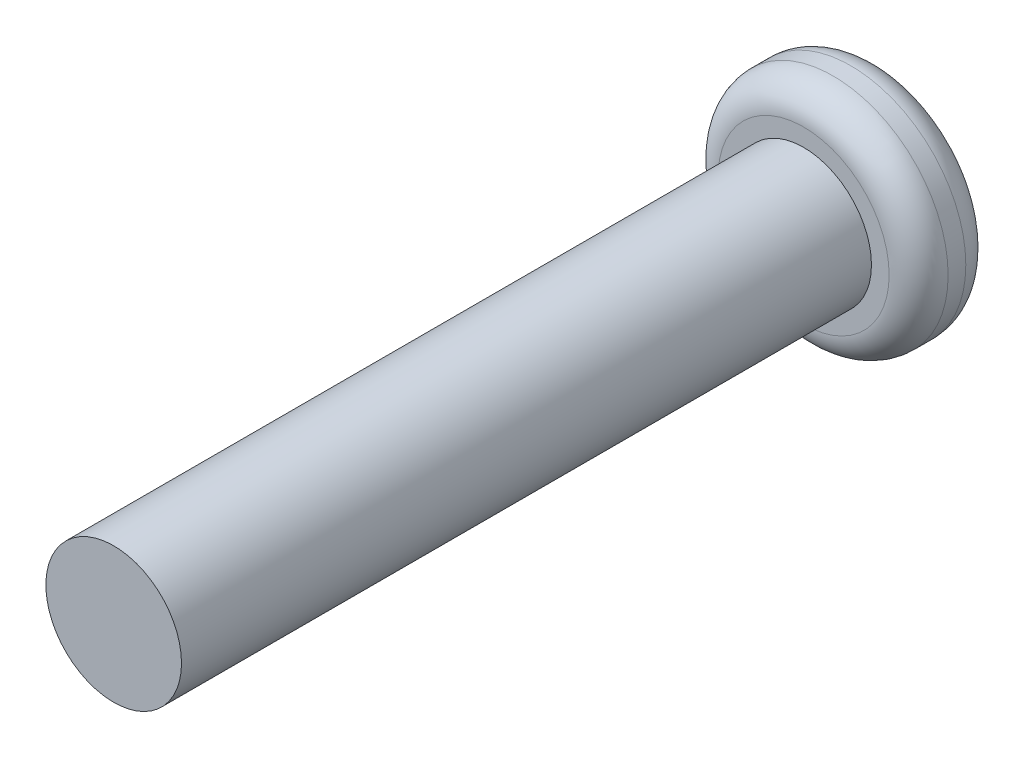
SolidWorks part; units mm, degrees
material "AISI 316 Annealed Stainless Steel Bar (SS)"
ref_plane "Front Plane" through (0, 0, 0) normal (0, 0, 1) x (1, 0, 0)
ref_plane "Top Plane" through (0, 0, 0) normal (0, 1, 0) x (1, 0, 0)
ref_plane "Right Plane" through (0, 0, 0) normal (1, 0, 0) x (0, 0, -1)
sketch "Sketch1" plane through (0, 0, 0) normal (0, 0, 1) x (1, 0, 0)
  circle A0 centre (0, 0) radius 1.95
  dimension "D1" = 3.9
extrude "Boss-Extrude1" add sketch "Sketch1" along normal blind 1.3
sketch "Sketch2" plane through (0, 0, 0) normal (0, 0, -1) x (-1, 0, 0)
  line L0 (0, 0) -> (0, 1.25) construction
  line L1 (-0.15, 1.25) -> (0.15, 1.25)
  line L2 (0.35, 1.05) -> (0.35, 0.55)
  line L3 (0.55, 0.35) -> (1.05, 0.35)
  line L4 (1.25, 0.15) -> (1.25, -0.15)
  line L5 (1.25, 0) -> (0, 0) construction
  line L6 (-1.25, 0.15) -> (-1.25, -0.15)
  line L7 (-0.55, 0.35) -> (-1.05, 0.35)
  line L8 (-0.35, 1.05) -> (-0.35, 0.55)
  line L9 (-0.35, -1.05) -> (-0.35, -0.55)
  line L10 (-0.55, -0.35) -> (-1.05, -0.35)
  line L11 (0.55, -0.35) -> (1.05, -0.35)
  line L12 (0.35, -1.05) -> (0.35, -0.55)
  line L13 (-0.15, -1.25) -> (0.15, -1.25)
  arc A0 (-0.55, 0.35) -> (-0.35, 0.55) centre (-0.55, 0.55) ccw
  arc A1 (-1.25, 0.15) -> (-1.05, 0.35) centre (-1.05, 0.15) cw
  arc A2 (-1.05, -0.35) -> (-1.25, -0.15) centre (-1.05, -0.15) cw
  arc A3 (-0.35, -0.55) -> (-0.55, -0.35) centre (-0.55, -0.55) ccw
  arc A4 (-0.35, -1.05) -> (-0.15, -1.25) centre (-0.15, -1.05) ccw
  arc A5 (0.35, -1.05) -> (0.15, -1.25) centre (0.15, -1.05) cw
  arc A6 (0.55, -0.35) -> (0.35, -0.55) centre (0.55, -0.55) ccw
  arc A7 (1.05, -0.35) -> (1.25, -0.15) centre (1.05, -0.15) ccw
  arc A8 (1.05, 0.35) -> (1.25, 0.15) centre (1.05, 0.15) cw
  arc A9 (0.35, 0.55) -> (0.55, 0.35) centre (0.55, 0.55) ccw
  arc A10 (0.15, 1.25) -> (0.35, 1.05) centre (0.15, 1.05) cw
  arc A11 (-0.35, 1.05) -> (-0.15, 1.25) centre (-0.15, 1.05) cw
  point P14 (-1.25, 0)
  point P19 (-0.35, 0.35)
  point P22 (-1.25, 0.35)
  point P25 (-1.25, -0.35)
  point P28 (-0.35, -0.35)
  point P31 (-0.35, -1.25)
  point P34 (0.35, -1.25)
  point P37 (0.35, -0.35)
  point P40 (1.25, -0.35)
  point P43 (1.25, 0.35)
  point P46 (0.35, 0.35)
  point P49 (0.35, 1.25)
  point P52 (-0.35, 1.25)
  dimension "D3" = 0.2
  dimension "D1" = 1.25
  dimension "D2" = 0.35
extrude "Cut-Extrude1" cut sketch "Sketch2" against normal blind 1
sketch "Sketch3" plane through (0, 0, 1.3) normal (0, 0, 1) x (1, 0, 0)
  circle A0 centre (0, 0) radius 1.15
  dimension "D1" = 2.3
extrude "Boss-Extrude2" add sketch "Sketch3" along normal blind 11.7
fillet "Fillet1" radius 0.5 2 edges at (1.95, 0, 0) (1.95, 0, 1.3)
